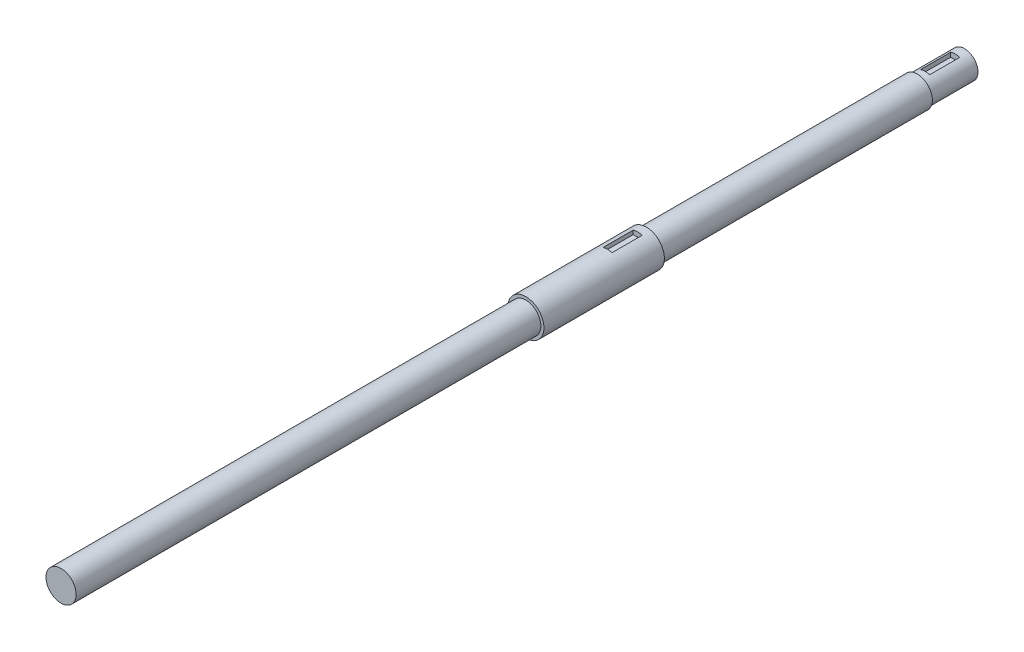
SolidWorks part; units mm, degrees
ref_plane "Front Plane" through (0, 0, 0) normal (0, 0, 1) x (1, 0, 0)
ref_plane "Top Plane" through (0, 0, 0) normal (0, 1, 0) x (1, 0, 0)
ref_plane "Right Plane" through (0, 0, 0) normal (1, 0, 0) x (0, 0, -1)
sketch "Sketch1" plane through (0, 0, 0) normal (1, 0, 0) x (0, 0, -1)
  line L0 (-134.9921, 0) -> (165.0079, 0)
  line L1 (-134.9921, 0) -> (-134.9921, 5)
  line L2 (165.0079, 0) -> (165.0079, 4.5)
  line L3 (165.0079, 4.5) -> (149.3574, 4.5)
  line L4 (149.3574, 4.5) -> (149.3574, 5)
  line L5 (149.3574, 5) -> (59.3574, 5)
  line L6 (59.3574, 5) -> (59.3574, 6)
  line L7 (59.3574, 6) -> (19.3574, 6)
  line L8 (19.3574, 6) -> (19.3574, 5)
  line L9 (-134.9921, 5) -> (19.3574, 5)
  dimension "D1" = 300
  dimension "D2" = 5
  dimension "D3" = 4.5
  dimension "D4" = 0.5
  dimension "D5" = 90
  dimension "D6" = 1
  dimension "D7" = 40
  dimension "D8" = 1
revolve "Revolve1" add sketch "Sketch1" angle 360 about L0
sketch "Sketch7" plane through (0, 0, 0) normal (1, 0, 0) x (0, 0, -1)
  line L0 (59.3574, 6) -> (19.3574, 6) construction
  line L1 (56.5122, 6) -> (46.5122, 6)
  line L2 (56.5122, 6) -> (56.5122, 4.5)
  line L3 (56.5122, 4.5) -> (46.5122, 4.5)
  line L4 (46.5122, 6) -> (46.5122, 4.5)
  dimension "D1" = 1.5
  dimension "D2" = 10
extrude "Cut-Extrude4" cut sketch "Sketch7" against normal mid plane 3
sketch "Sketch8" plane through (0, 0, 0) normal (1, 0, 0) x (0, 0, -1)
  line L0 (165.0079, 4.5) -> (149.3574, 4.5) construction
  line L1 (161.9345, 4.5) -> (151.9345, 4.5)
  line L2 (161.9345, 4.5) -> (161.9345, 2.8)
  line L3 (161.9345, 2.8) -> (151.9345, 2.8)
  line L4 (151.9345, 4.5) -> (151.9345, 2.8)
  dimension "D1" = 10
  dimension "D2" = 1.7
extrude "Cut-Extrude5" cut sketch "Sketch8" against normal mid plane 3
